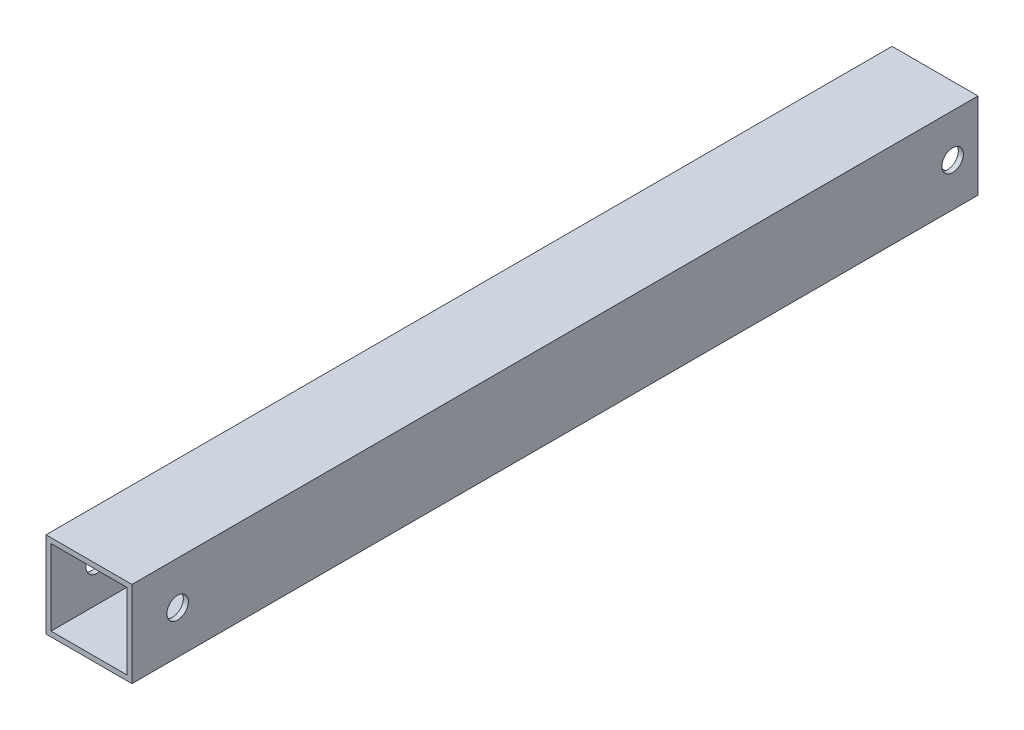
SolidWorks part; units mm, degrees
ref_plane "Alzado" through (0, 0, 0) normal (0, 0, 1) x (1, 0, 0)
ref_plane "Planta" through (0, 0, 0) normal (0, 1, 0) x (1, 0, 0)
ref_plane "Vista lateral" through (0, 0, 0) normal (1, 0, 0) x (0, 0, -1)
sketch "Croquis1" plane through (0, 0, 0) normal (0, 0, 1) x (1, 0, 0)
  line L0 (-22.4, 22.4) -> (22.4, 22.4)
  line L1 (-25.4, -25.4) -> (25.4, -25.4)
  line L2 (-25.4, -25.4) -> (-25.4, 25.4)
  line L3 (-25.4, 25.4) -> (25.4, 25.4)
  line L4 (25.4, -25.4) -> (25.4, 25.4)
  line L5 (-25.4, -25.4) -> (25.4, 25.4) construction
  line L6 (-25.4, 25.4) -> (25.4, -25.4) construction
  line L7 (22.4, -22.4) -> (22.4, 22.4)
  line L8 (-22.4, -22.4) -> (22.4, -22.4)
  line L9 (-22.4, -22.4) -> (-22.4, 22.4)
  point P0 (0, 0)
  dimension "D1" = 50.8
  dimension "D2" = 50.8
  dimension "D3" = 3
extrude "Saliente-Extruir1" add sketch "Croquis1" along normal mid plane 500
sketch "Croquis2" plane through (25.4, 0, 0) normal (1, 0, 0) x (0, 0, -1)
  line L0 (-250, 0) -> (250, 0) construction
  line L1 (-250, -25.4) -> (-250, 25.4) construction
  line L2 (250, -25.4) -> (250, 25.4) construction
  line L3 (-250, -25.4) -> (250, -25.4) construction
  line L4 (-223, 25.4) -> (-223, -25.4) construction
  line L5 (-250, 25.4) -> (250, 25.4) construction
  line L6 (0, 25.4) -> (0, -25.4) construction
  circle A0 centre (-223, 0) radius 6.35
  circle A1 centre (235, 0) radius 6.35
  point P18 (-250, 0)
  point P19 (0, 0)
  point P20 (235, 11.814)
  dimension "D3" = 12.7
  dimension "D1" = 12.7
  dimension "D2" = 27
  dimension "D4" = 15
extrude "Cortar-Extruir1" cut sketch "Croquis2" against normal through all
